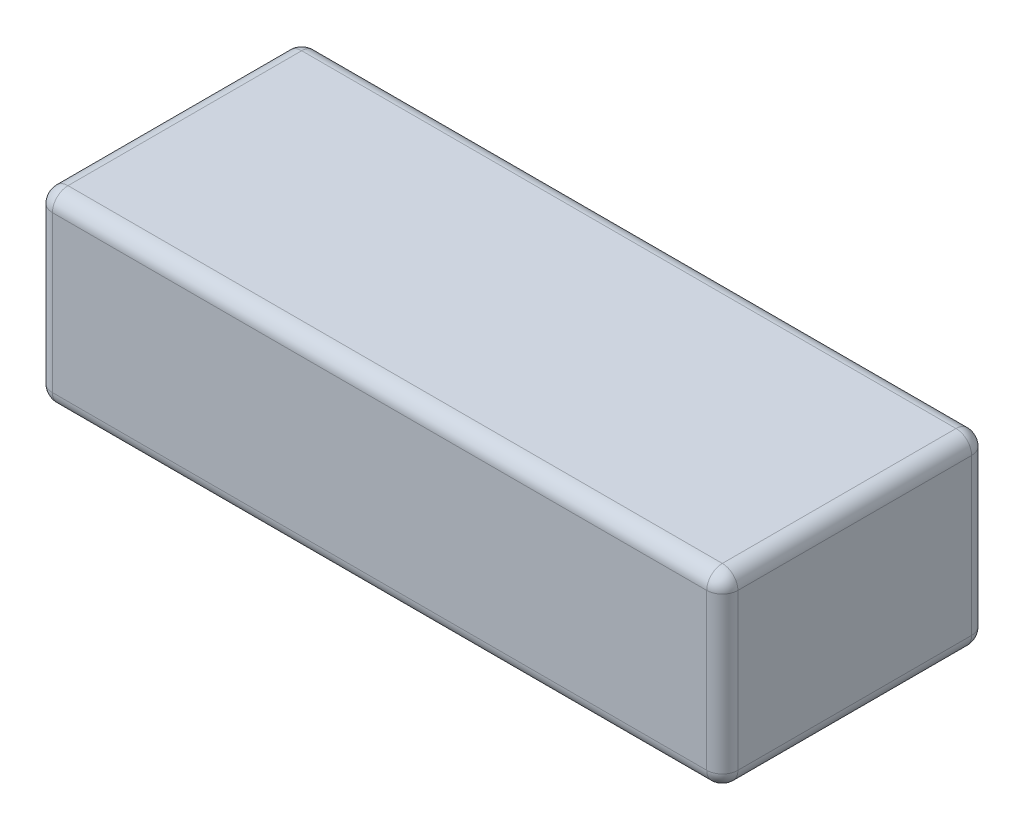
SolidWorks part; units mm, degrees
ref_plane "Front Plane" through (0, 0, 0) normal (0, 0, 1) x (1, 0, 0)
ref_plane "Top Plane" through (0, 0, 0) normal (0, 1, 0) x (1, 0, 0)
ref_plane "Right Plane" through (0, 0, 0) normal (1, 0, 0) x (0, 0, -1)
sketch "Sketch1" plane through (0, 0, 0) normal (0, 1, 0) x (1, 0, 0)
  line L1 (-22, 8.5) -> (22, 8.5)
  line L2 (-22, 8.5) -> (-22, -8.5)
  line L3 (-22, -8.5) -> (22, -8.5)
  line L4 (22, 8.5) -> (22, -8.5)
  line L5 (-22, 8.5) -> (22, -8.5) construction
  line L6 (-22, -8.5) -> (22, 8.5) construction
  point P0 (0, 0)
  dimension "D1" = 17
  dimension "D2" = 44
extrude "Boss-Extrude1" add sketch "Sketch1" along normal blind 12
fillet "Fillet1" radius 1 12 edges at (22, 0, 0) (0, 0, 8.5) (22, 12, 0) (0, 12, -8.5) (-22, 12, 0) (0, 12, 8.5) (22, 6, 8.5) (-22, 6, 8.5) (22, 6, -8.5) (0, 0, -8.5) (-22, 6, -8.5) (-22, 0, 0)
sketch "Sketch2" plane through (0, 0, 0) normal (0, -1, 0) x (1, 0, 0)
  line L0 (21, -8.5) -> (-22, -8.5) construction
  line L1 (20, -6.5) -> (-20, -6.5)
  line L2 (20, -6.5) -> (20, 6.5)
  line L3 (20, 6.5) -> (-20, 6.5)
  line L4 (-20, -6.5) -> (-20, 6.5)
  line L5 (20, -6.5) -> (-20, 6.5) construction
  line L6 (20, 6.5) -> (-20, -6.5) construction
  line L7 (-22, -8.5) -> (-22, 7.5) construction
  point P0 (0, 0)
  dimension "D1" = 2
  dimension "D2" = 2
extrude "Boss-Extrude2" add sketch "Sketch2" along normal blind 0.6
